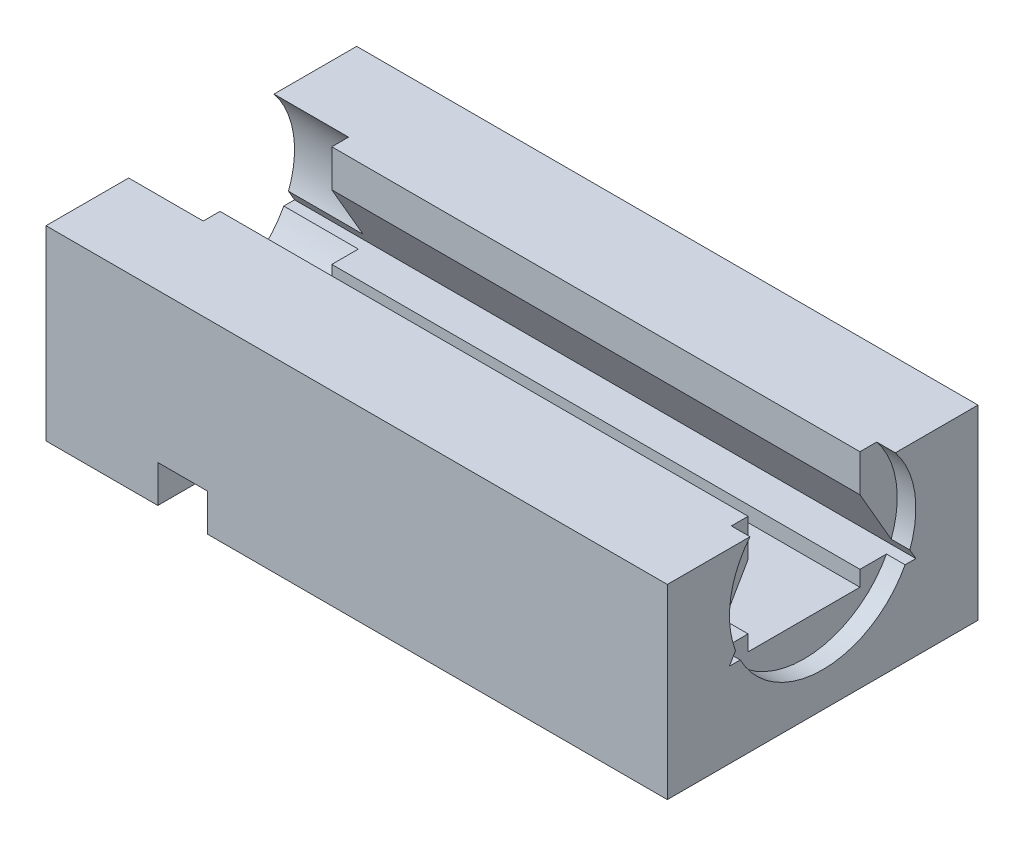
SolidWorks part; units mm, degrees
material "Polyetheretherketone (PEEK)"
ref_plane "Front Plane" through (0, 0, 0) normal (0, 0, 1) x (1, 0, 0)
ref_plane "Top Plane" through (0, 0, 0) normal (0, 1, 0) x (1, 0, 0)
ref_plane "Right Plane" through (0, 0, 0) normal (1, 0, 0) x (0, 0, -1)
ref_plane "Plane1" through (0, 4, 0) normal (0, 1, 0) x (-1, 0, 0)
sketch "Sketch1" plane through (0, 4, 0) normal (0, 1, 0) x (-1, 0, 0)
  line L0 (0, 0) -> (0, 5)
  line L1 (0, 5) -> (-10, 5)
  line L2 (-10, 5) -> (-10, 0)
  line L3 (-10, 0) -> (0, 0)
  dimension "D1" = 5
  dimension "D2" = 10
extrude "Boss-Extrude1" add sketch "Sketch1" against normal blind 3
sketch "Sketch18" plane through (10, 0, 0) normal (1, 0, 0) x (0, 0, -1)
  line L0 (-3.4, 3.4) -> (-4, 2.3608)
  line L1 (-5, 1) -> (-5, 4) construction
  line L2 (-4, 2.3608) -> (-3.4, 2.3608)
  line L3 (-3.4, 2.3608) -> (-3.4, 2.1108)
  line L4 (-1, 2.3608) -> (-1.6, 3.4)
  line L5 (-5, 4) -> (0, 4) construction
  line L6 (-3.4, 3.4) -> (-3.4, 4)
  line L7 (-3.4, 4) -> (-1.6, 4)
  line L8 (-3.4, 2.1108) -> (-1.6, 2.1108)
  line L9 (-1.6, 4) -> (-1.6, 3.4)
  line L10 (-1.6, 2.1108) -> (-1.6, 2.3608)
  line L11 (-1.6, 2.3608) -> (-1, 2.3608)
  dimension "D1" = 60
  dimension "D2" = 1.6
  dimension "D3" = 0.25
  dimension "D4" = 1.8
  dimension "D5" = 0.6
  dimension "D6" = 3
  dimension "D7" = 1.0392
extrude "Cut-Extrude9" cut sketch "Sketch18" against normal through all
sketch "Sketch20" plane through (0, 0, 0) normal (-1, 0, 0) x (0, 0, 1)
  line L0 (1.6, 2.3608) -> (1, 2.3608) construction
  circle A1 centre (2.5, 3.0608) radius 1.5
  dimension "D1" = 0.7
extrude "Cut-Extrude11" cut sketch "Sketch20" against normal blind 1.2
sketch "Sketch22" plane through (10, 0, 0) normal (1, 0, 0) x (0, 0, -1)
  circle A0 centre (-2.5, 3.0608) radius 1.5
  arc A1 (-3.8266, 2.3608) -> (-1.1734, 2.3608) centre (-2.5, 3.0608) ccw construction
  circle A2 centre (-2.5, 3.0608) radius 0.55
extrude "Cut-Extrude12" cut sketch "Sketch22" against normal blind 0.3
sketch "Sketch24" plane through (0, 0, 5) normal (0, 0, 1) x (1, 0, 0)
  line L0 (1.8, 1) -> (1.8, 1.6)
  line L4 (0, 1) -> (0, 4) construction
  line L5 (1.8, 1.6) -> (2.6, 1.6)
  line L6 (2.6, 1.6) -> (2.6, 1)
  line L7 (2.6, 1) -> (1.8, 1)
  point P2 (0, 0)
  point P6 (0, 0)
  dimension "D1" = 1.8
extrude "Cut-Extrude13" cut sketch "Sketch24" against normal through all
